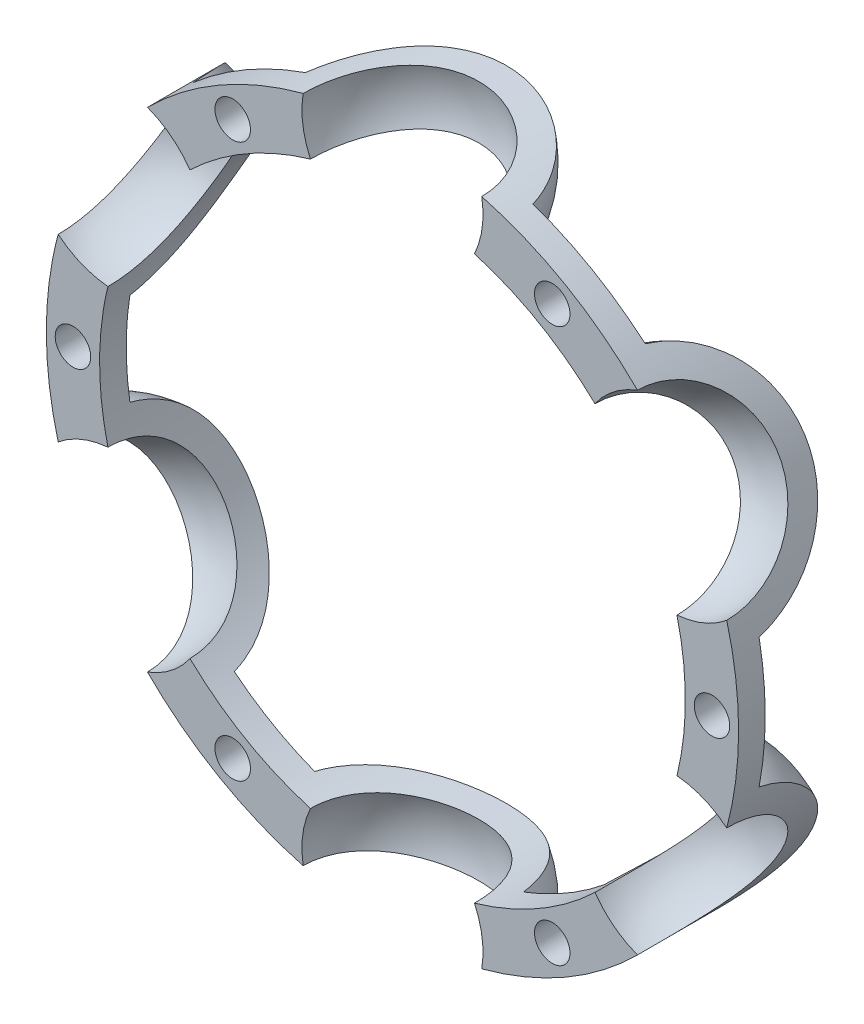
SolidWorks part; units mm, degrees
material "1060 Alloy"
ref_plane "Front Plane" through (0, 0, 0) normal (0, 0, 1) x (1, 0, 0)
ref_plane "Top Plane" through (0, 0, 0) normal (0, 1, 0) x (1, 0, 0)
ref_plane "Right Plane" through (0, 0, 0) normal (1, 0, 0) x (0, 0, -1)
sketch "Sketch1" plane through (0, 0, 0) normal (0, 0, 1) x (1, 0, 0)
  circle A0 centre (0, 0) radius 9.75
  circle A1 centre (0, 0) radius 9 construction
  circle A2 centre (0, 0) radius 8.25
  dimension "D1" = 16.5
  dimension "D2" = 18
  dimension "D3" = 19.5
extrude "Boss-Extrude1" add sketch "Sketch1" along normal mid plane 5
sketch "Sketch2" plane through (0, 0, 2.5) normal (0, 0, 1) x (1, 0, 0)
  line L0 (0, 0) -> (0, 10.1254) construction
  line L1 (0, 6.45) -> (0, 11.55)
  arc A0 (0, 6.45) -> (0, 11.55) centre (0, 9) ccw
  circle A1 centre (0, 0) radius 9 construction
  dimension "D1" = 2.55
revolve "Cut-Revolve1" cut sketch "Sketch2" angle 360 about L0
pattern_circular "CirPattern1" count 6 over 360 about axis through (0, 0, 0) along (0, 0, 1) of "Cut-Revolve1"
shell "Shell1" thickness 0.75
sketch "Sketch3" plane through (0, 0, 2.5) normal (0, 0, 1) x (1, 0, 0)
  line L0 (0, 0) -> (13.1287, 0) construction
  circle A0 centre (0, 0) radius 9 construction
  circle A1 centre (9, 0) radius 0.5
  dimension "D1" = 18
  dimension "D2" = 1
extrude "Cut-Extrude2" cut sketch "Sketch3" against normal through all
pattern_circular "CirPattern2" count 6 over 360 about axis through (0, 0, 0) along (0, 0, 1) of "Cut-Extrude2"
